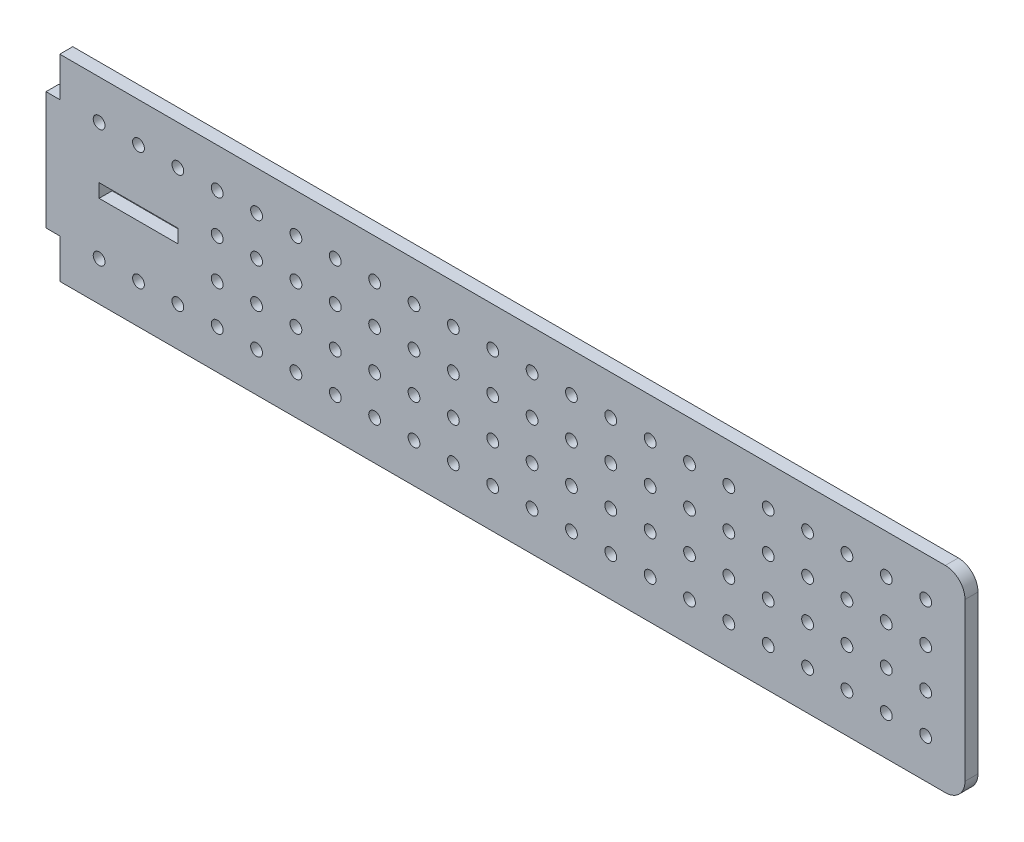
SolidWorks part; units mm, degrees
material "Pine"
ref_plane "Front Plane" through (0, 0, 0) normal (0, 0, 1) x (1, 0, 0)
ref_plane "Top Plane" through (0, 0, 0) normal (0, 1, 0) x (1, 0, 0)
ref_plane "Right Plane" through (0, 0, 0) normal (1, 0, 0) x (0, 0, -1)
sketch "Sketch1" plane through (0, 0, 0) normal (0, 0, 1) x (1, 0, 0)
  line L0 (-115, 25) -> (110, 25)
  line L6 (-115, -25) -> (110, -25)
  line L7 (115, 20) -> (115, -20)
  line L8 (-115, 25) -> (115, -25) construction
  line L9 (-115, -25) -> (115, 25) construction
  line L10 (-115, -15) -> (-105, -15) construction
  line L11 (-105, -15) -> (-95, -15) construction
  line L12 (-95, -15) -> (-85, -15) construction
  line L13 (-85, -15) -> (-75, -15) construction
  line L14 (-75, -15) -> (-65, -15) construction
  line L15 (-65, -15) -> (-55, -15) construction
  line L16 (-55, -15) -> (-45, -15) construction
  line L17 (-45, -15) -> (-35, -15) construction
  line L18 (-35, -15) -> (-25, -15) construction
  line L19 (-25, -15) -> (-15, -15) construction
  line L20 (-15, -15) -> (-5, -15) construction
  line L21 (-5, -15) -> (5, -15) construction
  line L22 (5, -15) -> (15, -15) construction
  line L23 (15, -15) -> (25, -15) construction
  line L24 (25, -15) -> (35, -15) construction
  line L25 (35, -15) -> (45, -15) construction
  line L26 (45, -15) -> (55, -15) construction
  line L27 (55, -15) -> (65, -15) construction
  line L28 (65, -15) -> (75, -15) construction
  line L29 (75, -15) -> (85, -15) construction
  line L30 (85, -15) -> (95, -15) construction
  line L31 (95, -15) -> (105, -15) construction
  line L32 (-115, -5) -> (-105, -5) construction
  line L33 (-105, -5) -> (-95, -5) construction
  line L34 (-95, -5) -> (-85, -5) construction
  line L35 (-85, -5) -> (-75, -5) construction
  line L36 (-75, -5) -> (-65, -5) construction
  line L37 (-65, -5) -> (-55, -5) construction
  line L38 (-55, -5) -> (-45, -5) construction
  line L39 (-45, -5) -> (-35, -5) construction
  line L40 (-35, -5) -> (-25, -5) construction
  line L41 (-25, -5) -> (-15, -5) construction
  line L42 (-15, -5) -> (-5, -5) construction
  line L43 (-5, -5) -> (5, -5) construction
  line L44 (5, -5) -> (15, -5) construction
  line L45 (15, -5) -> (25, -5) construction
  line L46 (25, -5) -> (35, -5) construction
  line L47 (35, -5) -> (45, -5) construction
  line L48 (45, -5) -> (55, -5) construction
  line L49 (55, -5) -> (65, -5) construction
  line L50 (65, -5) -> (75, -5) construction
  line L51 (75, -5) -> (85, -5) construction
  line L52 (85, -5) -> (95, -5) construction
  line L53 (95, -5) -> (105, -5) construction
  line L54 (-115, 5) -> (-105, 5) construction
  line L55 (-105, 5) -> (-95, 5) construction
  line L56 (-95, 5) -> (-85, 5) construction
  line L57 (-85, 5) -> (-75, 5) construction
  line L58 (-75, 5) -> (-65, 5) construction
  line L59 (-65, 5) -> (-55, 5) construction
  line L60 (-55, 5) -> (-45, 5) construction
  line L61 (-45, 5) -> (-35, 5) construction
  line L62 (-35, 5) -> (-25, 5) construction
  line L63 (-25, 5) -> (-15, 5) construction
  line L64 (-15, 5) -> (-5, 5) construction
  line L65 (-5, 5) -> (5, 5) construction
  line L66 (5, 5) -> (15, 5) construction
  line L67 (15, 5) -> (25, 5) construction
  line L68 (25, 5) -> (35, 5) construction
  line L69 (35, 5) -> (45, 5) construction
  line L70 (45, 5) -> (55, 5) construction
  line L71 (55, 5) -> (65, 5) construction
  line L72 (65, 5) -> (75, 5) construction
  line L73 (75, 5) -> (85, 5) construction
  line L74 (85, 5) -> (95, 5) construction
  line L75 (95, 5) -> (105, 5) construction
  line L76 (-115, 15) -> (-105, 15) construction
  line L77 (-105, 15) -> (-95, 15) construction
  line L78 (-95, 15) -> (-85, 15) construction
  line L79 (-85, 15) -> (-75, 15) construction
  line L80 (-75, 15) -> (-65, 15) construction
  line L81 (-65, 15) -> (-55, 15) construction
  line L82 (-55, 15) -> (-45, 15) construction
  line L83 (-45, 15) -> (-35, 15) construction
  line L84 (-35, 15) -> (-25, 15) construction
  line L85 (-25, 15) -> (-15, 15) construction
  line L86 (-15, 15) -> (-5, 15) construction
  line L87 (-5, 15) -> (5, 15) construction
  line L88 (5, 15) -> (15, 15) construction
  line L89 (15, 15) -> (25, 15) construction
  line L90 (25, 15) -> (35, 15) construction
  line L91 (35, 15) -> (45, 15) construction
  line L92 (45, 15) -> (55, 15) construction
  line L93 (55, 15) -> (65, 15) construction
  line L94 (65, 15) -> (75, 15) construction
  line L95 (75, 15) -> (85, 15) construction
  line L96 (85, 15) -> (95, 15) construction
  line L97 (95, 15) -> (105, 15) construction
  line L98 (0, 0) -> (-50000, 0) construction
  line L99 (-105, 1.725) -> (-105, -1.725)
  line L100 (-105, -1.725) -> (-85, -1.725)
  line L101 (-85, -1.725) -> (-85, 1.725)
  line L102 (-85, 1.725) -> (-105, 1.725)
  line L103 (-115, 25) -> (-115, 15)
  line L104 (-115, 15) -> (-118.5, 15)
  line L105 (-118.5, 15) -> (-118.5, -15)
  line L106 (-118.5, -15) -> (-115, -15)
  line L107 (-115, -15) -> (-115, -25)
  arc A4 (115, -20) -> (110, -25) centre (110, -20) cw
  arc A5 (115, 20) -> (110, 25) centre (110, 20) ccw
  circle A8 centre (-105, -15) radius 1.5
  circle A9 centre (-95, -15) radius 1.5
  circle A10 centre (-85, -15) radius 1.5
  circle A11 centre (-75, -15) radius 1.5
  circle A12 centre (-65, -15) radius 1.5
  circle A13 centre (-55, -15) radius 1.5
  circle A14 centre (-45, -15) radius 1.5
  circle A15 centre (-35, -15) radius 1.5
  circle A16 centre (-25, -15) radius 1.5
  circle A17 centre (-15, -15) radius 1.5
  circle A18 centre (-5, -15) radius 1.5
  circle A19 centre (15, -15) radius 1.5
  circle A20 centre (25, -15) radius 1.5
  circle A21 centre (5, -15) radius 1.5
  circle A22 centre (35, -15) radius 1.5
  circle A23 centre (45, -15) radius 1.5
  circle A24 centre (55, -15) radius 1.5
  circle A25 centre (65, -15) radius 1.5
  circle A26 centre (75, -15) radius 1.5
  circle A27 centre (85, -15) radius 1.5
  circle A28 centre (95, -15) radius 1.5
  circle A29 centre (105, -15) radius 1.5
  circle A33 centre (-75, -5) radius 1.5
  circle A34 centre (-65, -5) radius 1.5
  circle A35 centre (-55, -5) radius 1.5
  circle A36 centre (-45, -5) radius 1.5
  circle A37 centre (-35, -5) radius 1.5
  circle A38 centre (-25, -5) radius 1.5
  circle A39 centre (-15, -5) radius 1.5
  circle A40 centre (-5, -5) radius 1.5
  circle A41 centre (15, -5) radius 1.5
  circle A42 centre (25, -5) radius 1.5
  circle A43 centre (5, -5) radius 1.5
  circle A44 centre (35, -5) radius 1.5
  circle A45 centre (45, -5) radius 1.5
  circle A46 centre (55, -5) radius 1.5
  circle A47 centre (65, -5) radius 1.5
  circle A48 centre (75, -5) radius 1.5
  circle A49 centre (85, -5) radius 1.5
  circle A50 centre (95, -5) radius 1.5
  circle A51 centre (105, -5) radius 1.5
  circle A55 centre (-75, 5) radius 1.5
  circle A56 centre (-65, 5) radius 1.5
  circle A57 centre (-55, 5) radius 1.5
  circle A58 centre (-45, 5) radius 1.5
  circle A59 centre (-35, 5) radius 1.5
  circle A60 centre (-25, 5) radius 1.5
  circle A61 centre (-15, 5) radius 1.5
  circle A62 centre (-5, 5) radius 1.5
  circle A63 centre (15, 5) radius 1.5
  circle A64 centre (25, 5) radius 1.5
  circle A65 centre (5, 5) radius 1.5
  circle A66 centre (35, 5) radius 1.5
  circle A67 centre (45, 5) radius 1.5
  circle A68 centre (55, 5) radius 1.5
  circle A69 centre (65, 5) radius 1.5
  circle A70 centre (75, 5) radius 1.5
  circle A71 centre (85, 5) radius 1.5
  circle A72 centre (95, 5) radius 1.5
  circle A73 centre (105, 5) radius 1.5
  circle A74 centre (-105, 15) radius 1.5
  circle A75 centre (-95, 15) radius 1.5
  circle A76 centre (-85, 15) radius 1.5
  circle A77 centre (-75, 15) radius 1.5
  circle A78 centre (-65, 15) radius 1.5
  circle A79 centre (-55, 15) radius 1.5
  circle A80 centre (-45, 15) radius 1.5
  circle A81 centre (-35, 15) radius 1.5
  circle A82 centre (-25, 15) radius 1.5
  circle A83 centre (-15, 15) radius 1.5
  circle A84 centre (-5, 15) radius 1.5
  circle A85 centre (15, 15) radius 1.5
  circle A86 centre (25, 15) radius 1.5
  circle A87 centre (5, 15) radius 1.5
  circle A88 centre (35, 15) radius 1.5
  circle A89 centre (45, 15) radius 1.5
  circle A90 centre (55, 15) radius 1.5
  circle A91 centre (65, 15) radius 1.5
  circle A92 centre (75, 15) radius 1.5
  circle A93 centre (85, 15) radius 1.5
  circle A94 centre (95, 15) radius 1.5
  circle A95 centre (105, 15) radius 1.5
  point P0 (0, 0)
  point P14 (0, 0)
  point P15 (0, 0)
  point P156 (-105, 0)
  dimension "D1" = 50
  dimension "D3" = 5
  dimension "D4" = 3
  dimension "D18" = 10
  dimension "D5" = 10
  dimension "D2" = 230
  dimension "D6" = 10
  dimension "D7" = 10
  dimension "D8" = 10
  dimension "D9" = 10
  dimension "D10" = 3.45
  dimension "D11" = 20
  dimension "D12" = 10
  dimension "D14" = 3.5
  dimension "D15" = 115
  dimension "D16" = 25
  dimension "D17" = 118.5
  dimension "D19" = 10
  dimension "D20" = 10
  dimension "D21" = 10
  dimension "D22" = 85
extrude "Boss-Extrude1" add sketch "Sketch1" along normal blind 3.3
